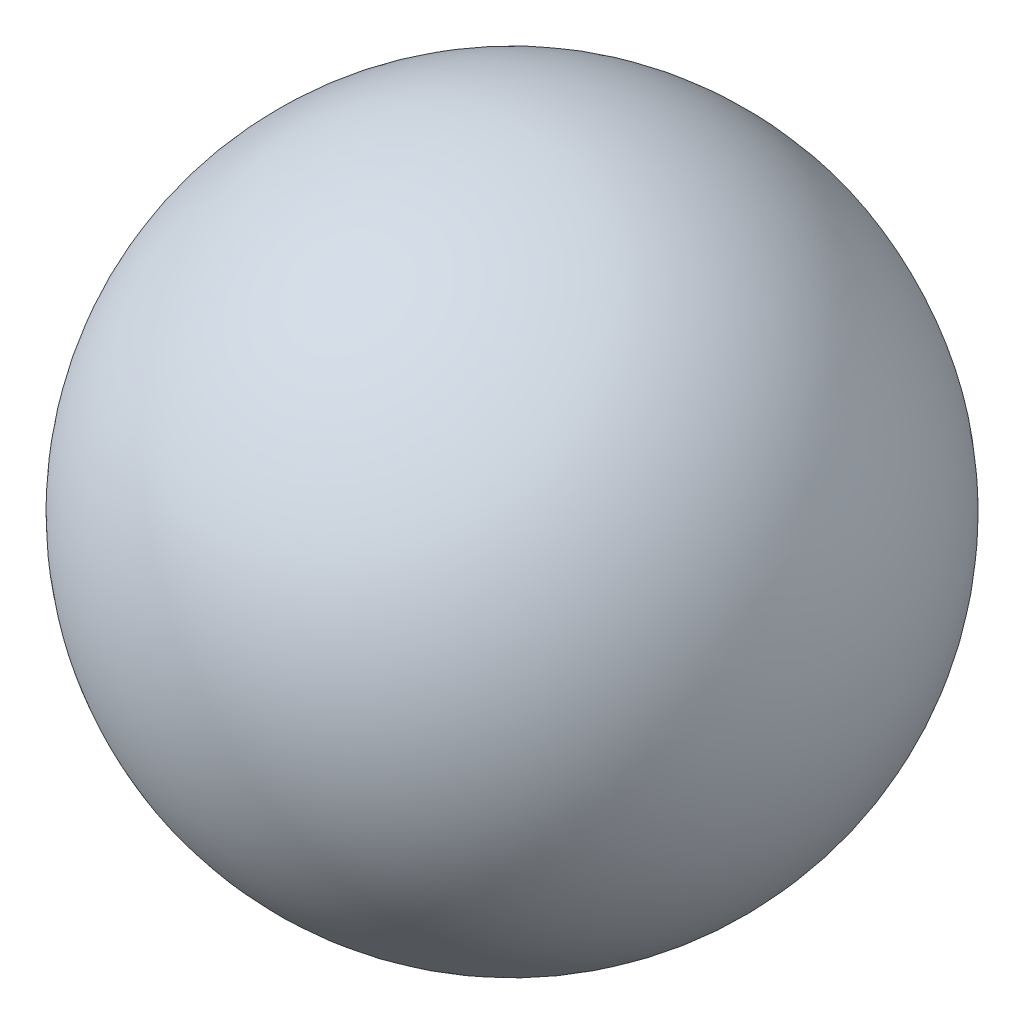
SolidWorks part; units mm, degrees
ref_plane "前视基准面" through (0, 0, 0) normal (0, 0, 1) x (1, 0, 0)
ref_plane "上视基准面" through (0, 0, 0) normal (0, 1, 0) x (1, 0, 0)
ref_plane "右视基准面" through (0, 0, 0) normal (1, 0, 0) x (0, 0, -1)
other "Configuration Table"
sketch "草图2" plane through (0, 0, 0) normal (0, 1, 0) x (1, 0, 0)
  line L0 (0, -56.2915) -> (0, -64.2457) construction
  line L7 (7.155, -36.6649) -> (6.8242, -37.8412)
  line L8 (0, -56.2915) -> (0, -56.8067)
  arc A11 (7.155, -36.6649) -> (0, -56.8067) centre (0, -45.4649) cw
  arc A12 (6.8242, -37.8412) -> (0, -56.2915) centre (0, -45.8043) cw
revolve "旋转1" add sketch "草图2" angle 360 about L0
